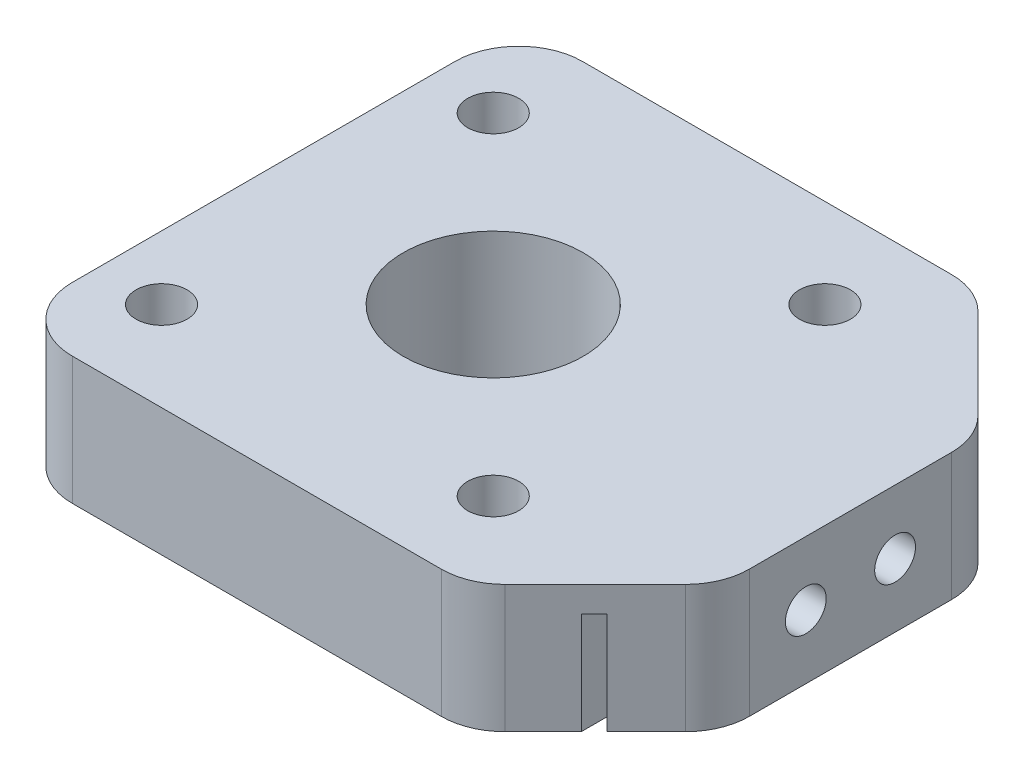
SolidWorks part; units mm, degrees
ref_plane "Front Plane" through (0, 0, 0) normal (0, 0, 1) x (1, 0, 0)
ref_plane "Top Plane" through (0, 0, 0) normal (0, 1, 0) x (1, 0, 0)
ref_plane "Right Plane" through (0, 0, 0) normal (1, 0, 0) x (0, 0, -1)
sketch "Sketch1" plane through (0, 0, 0) normal (0, 1, 0) x (1, 0, 0)
  line L0 (0, 20) -> (0, -20) construction
  line L1 (-18, -20) -> (18, -20)
  line L2 (-18, -20) -> (-18, 20)
  line L3 (-18, 20) -> (18, 20)
  line L4 (18, -20) -> (18, 20)
  line L5 (-18, -20) -> (18, 20) construction
  line L6 (-18, 20) -> (18, -20) construction
  line L7 (-18, 0) -> (18, 0) construction
  circle A0 centre (-13, 13) radius 2
  circle A1 centre (13, 13) radius 2
  circle A2 centre (-13, -13) radius 2
  circle A3 centre (13, -13) radius 2
  circle A4 centre (0, 0) radius 7.05
  point P0 (0, 0)
  dimension "D5" = 4
  dimension "D6" = 14.1
  dimension "D1" = 36
  dimension "D2" = 40
  dimension "D3" = 13
  dimension "D4" = 13
extrude "Boss-Extrude1" add sketch "Sketch1" along normal blind 10
sketch "Sketch3" plane through (0, 0, 0) normal (0, 1, 0) x (1, 0, 0)
  line L0 (18, 20) -> (18, -20)
  line L1 (-22.5772, 0) -> (49.0566, 0) construction
  line L2 (18, -20) -> (28, -10)
  line L3 (28, -10) -> (28, 10)
  line L4 (18, 20) -> (28, 10)
  point P10 (28, 0)
  dimension "D1" = 10
  dimension "D2" = 45
extrude "Boss-Extrude2" add sketch "Sketch3" along normal up to surface (10 mm away) up to face at (0, 10, 0)
fillet "Fillet1" radius 5 6 edges at (28, 5, 10) (28, 5, -10) (18, 5, -20) (18, 5, 20) (-18, 5, -20) (-18, 5, 20)
sketch "Sketch4" plane through (0, 0, 0) normal (0, 0, 1) x (1, 0, 0)
  line L0 (22.45, 0) -> (22.45, 8)
  line L1 (22.45, 8) -> (23.45, 8)
  line L2 (23.45, 8) -> (23.45, 0)
  line L3 (23.45, 0) -> (22.45, 0)
  line L4 (19.4645, 0) -> (26.5355, 0) construction
  dimension "D1" = 1
  dimension "D2" = 8
  dimension "D3" = 22.45
extrude "Cut-Extrude1" cut sketch "Sketch4" against normal through all both and the other way through all
sketch "Sketch5" plane through (28, 0, 0) normal (1, 0, 0) x (0, 0, -1)
  line L0 (0, 12.0565) -> (0, -1.7789) construction
  line L1 (-7.9289, 0) -> (7.9289, 0) construction
  circle A0 centre (-3.5, 5) radius 1.6
  circle A1 centre (3.5, 5) radius 1.6
  dimension "D1" = 3.2
  dimension "D2" = 5
  dimension "D3" = 3.5
extrude "Cut-Extrude2" cut sketch "Sketch5" against normal up to next
equation "\"14。1\"=14.1864"
